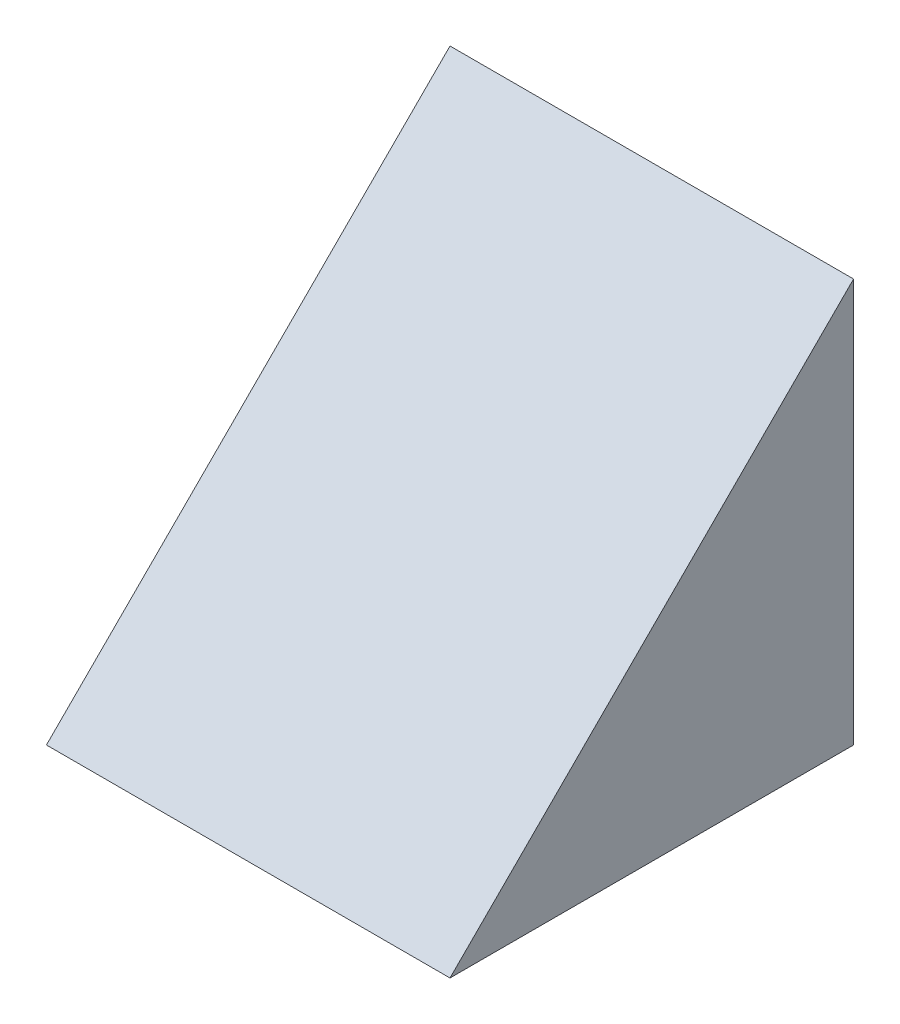
SolidWorks part; units mm, degrees
material "Glass"
ref_plane "Front Plane" through (0, 0, 0) normal (0, 0, 1) x (1, 0, 0)
ref_plane "Top Plane" through (0, 0, 0) normal (0, 1, 0) x (1, 0, 0)
ref_plane "Right Plane" through (0, 0, 0) normal (1, 0, 0) x (0, 0, -1)
sketch "Sketch1" plane through (0, 0, 0) normal (1, 0, 0) x (0, 0, -1)
  line L0 (-0.5, -0.5) -> (0.5, 0.5)
  line L3 (-0.5, -0.5) -> (0.5, -0.5)
  line L4 (0.5, 0.5) -> (0.5, -0.5)
  line L6 (-0.5, -0.5) -> (0.5, 0.5) construction
  point P0 (0, 0)
  dimension "D2" = 1
extrude "Boss-Extrude1" add sketch "Sketch1" along normal blind 1
